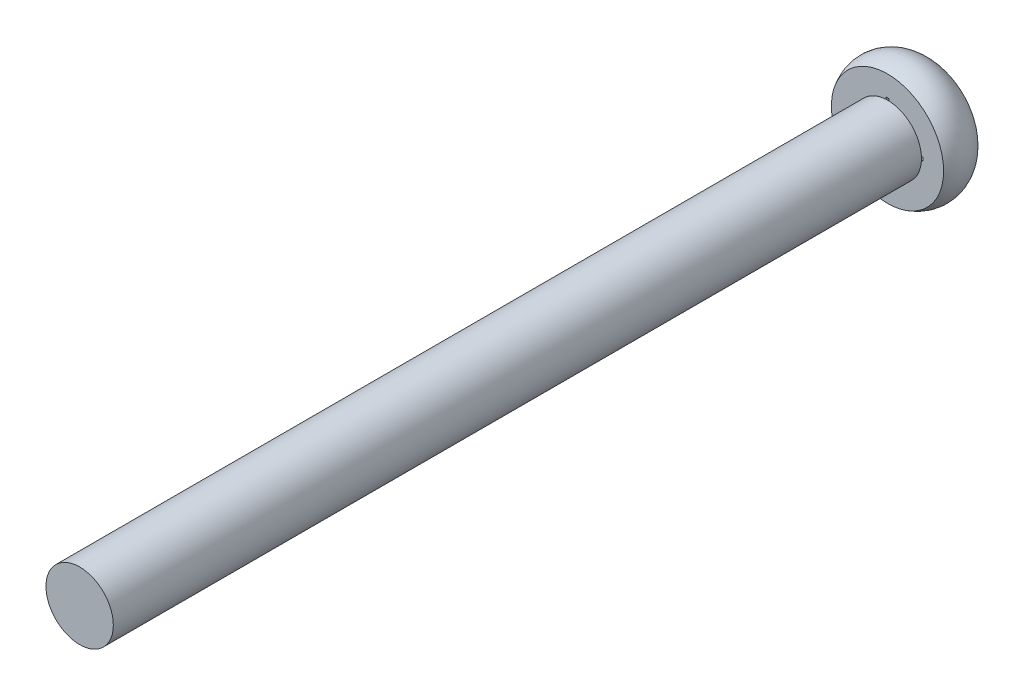
SolidWorks part; units mm, degrees
ref_plane "Front Plane" through (0, 0, 0) normal (0, 0, 1) x (1, 0, 0)
ref_plane "Top Plane" through (0, 0, 0) normal (0, 1, 0) x (1, 0, 0)
ref_plane "Right Plane" through (0, 0, 0) normal (1, 0, 0) x (0, 0, -1)
sketch "Sketch1" plane through (0, 0, 0) normal (0, 1, 0) x (1, 0, 0)
  line L0 (0, 0.6593) -> (0, 4.5218) construction
  line L3 (0, 0) -> (0, 2)
  line L4 (0, 0) -> (2.5, 0)
  line L5 (0, 2) -> (1.7983, 2)
  arc A0 (2.0735, 1.9174) -> (2.5, 0) centre (1.2961, 0.7384) cw
  arc A1 (2.0735, 1.9174) -> (1.7983, 2) centre (1.7983, 1.5) ccw
  dimension "D2" = 0.5
revolve "Revolve2" add sketch "Sketch1" angle 360 about L0
sketch "Sketch2" plane through (0, 0, -2) normal (0, 0, -1) x (-1, 0, 0)
  line L0 (0, 0) -> (2.5296, 0) construction
  line L1 (0, 0) -> (0, 1.7464) construction
  line L2 (0.5, -0.5) -> (2, -0.5)
  line L3 (-0.5, 2) -> (0.5, 2)
  line L4 (-0.5, 2) -> (-0.5, 0.5)
  line L5 (-0.5, -2) -> (0.5, -2)
  line L6 (0.5, 2) -> (0.5, 0.5)
  line L7 (0.5, 0.5) -> (2, 0.5)
  line L8 (0.5, -0.5) -> (0.5, -2)
  line L9 (-2, 0.5) -> (-0.5, 0.5)
  line L10 (-2, 0.5) -> (-2, -0.5)
  line L11 (-2, -0.5) -> (-0.5, -0.5)
  line L12 (2, 0.5) -> (2, -0.5)
  line L15 (-0.5, -0.5) -> (-0.5, -2)
  point P4 (0, 0)
  point P12 (0, 0)
  dimension "D1" = 0.5
  dimension "D2" = 2
  dimension "D3" = 2
  dimension "D4" = 2
  dimension "D5" = 0.5
  dimension "D6" = 0.5
  dimension "D7" = 0.5
  dimension "D8" = 0.5
extrude "Cut-Extrude1" cut sketch "Sketch2" against normal blind 2 draft 12
sketch "Sketch3" plane through (0, 0, 0) normal (0, 0, 1) x (1, 0, 0)
  circle A0 centre (0.0136, -0.0136) radius 1.5
extrude "Boss-Extrude1" add sketch "Sketch3" along normal blind 36
cosmetic thread "Cosmetic Thread2" parameters "D2"=2.439
